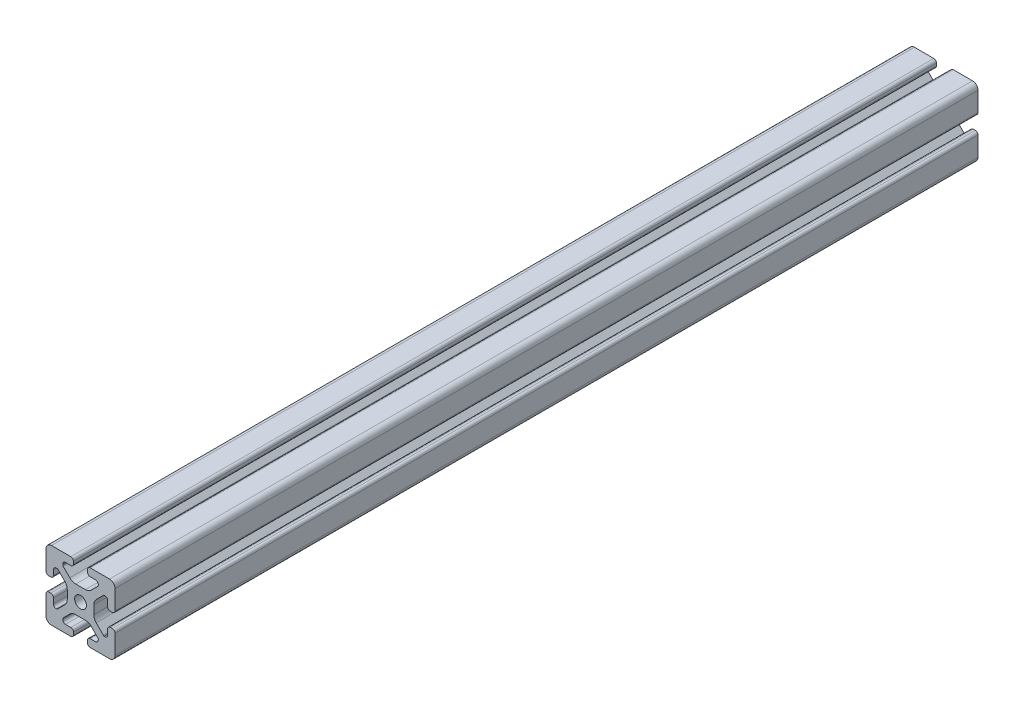
SolidWorks part; units mm, degrees
ref_plane "Front Plane" through (0, 0, 0) normal (0, 0, 1) x (1, 0, 0)
ref_plane "Top Plane" through (0, 0, 0) normal (0, 1, 0) x (1, 0, 0)
ref_plane "Right Plane" through (0, 0, 0) normal (1, 0, 0) x (0, 0, -1)
sketch "Sketch1" plane through (0, 0, 0) normal (0, 0, 1) x (1, 0, 0)
  line L0 (0, 19.7407) -> (0, -19.7407) construction
  line L1 (19.0335, 0) -> (-20.7246, 0) construction
  line L2 (-8.715, -15.5246) -> (-5.63, -15.5246)
  line L3 (-10.285, -13.9546) -> (-10.285, -13.4925)
  line L4 (-6.2171, -9.1098) -> (-10.0624, -12.9551)
  line L5 (2.7773, -7.685) -> (-2.7773, -7.685)
  line L6 (10.0624, -12.9551) -> (6.2171, -9.1098)
  line L7 (10.285, -13.9546) -> (10.285, -13.4925)
  line L8 (5.63, -15.5246) -> (8.715, -15.5246)
  line L9 (4.06, -18.43) -> (4.06, -17.0946)
  line L10 (-4.06, -18.43) -> (-4.06, -17.0946)
  line L11 (15.68, -8.7154) -> (15.68, -5.63)
  line L12 (-14.11, -10.2854) -> (-13.8169, -10.2854)
  line L13 (20, -16.83) -> (20, -5.63)
  line L14 (20, 5.63) -> (20, 13.0011)
  line L15 (-16.83, 20) -> (-5.63, 20)
  line L16 (5.63, 20) -> (12.9796, 20)
  line L17 (-8.715, 15.5246) -> (-5.63, 15.5246)
  line L18 (-20, -17.0184) -> (-20, -5.7579)
  line L19 (-20, 5.573) -> (-20, 13.0045)
  line L20 (-15.68, -8.7154) -> (-15.68, -5.7579)
  line L21 (-16.6746, -20) -> (-5.63, -20)
  line L22 (5.63, -20) -> (13, -20)
  line L23 (14.11, -10.2854) -> (13.6201, -10.2854)
  line L24 (13.1637, -9.947) -> (9.0762, -5.8595)
  line L25 (7.685, -2.5008) -> (7.685, 2.5008)
  line L26 (9.0762, 5.8595) -> (13.2795, 10.0628)
  line L27 (13.8169, 10.2854) -> (14.11, 10.2854)
  line L28 (15.68, 8.7154) -> (15.68, 5.63)
  line L29 (17.25, 4.06) -> (18.43, 4.06)
  line L30 (20, 13.0011) -> (20, 16.83)
  line L31 (16.83, 20) -> (12.9796, 20)
  line L32 (4.06, 18.43) -> (4.06, 17.0946)
  line L33 (5.63, 15.5246) -> (8.715, 15.5246)
  line L34 (10.285, 13.9546) -> (10.285, 13.4925)
  line L35 (10.0624, 12.9551) -> (6.2171, 9.1098)
  line L36 (2.7773, 7.685) -> (-2.7773, 7.685)
  line L37 (-6.2171, 9.1098) -> (-10.0624, 12.9551)
  line L38 (-10.285, 13.4925) -> (-10.285, 13.9546)
  line L39 (-4.06, 17.0946) -> (-4.06, 18.43)
  line L40 (-20, 16.83) -> (-20, 13.0045)
  line L41 (-18.43, 4.003) -> (-17.25, 4.003)
  line L42 (-15.68, 5.573) -> (-15.68, 8.4757)
  line L43 (-14.0552, 10.0447) -> (-13.7199, 10.033)
  line L44 (-13.0405, 9.8238) -> (-9.0762, 5.8595)
  line L45 (-7.685, 2.5008) -> (-7.685, -2.5008)
  line L46 (-9.0762, -5.8595) -> (-13.2795, -10.0628)
  line L47 (-17.2485, -4.1204) -> (-18.43, -4.1204)
  line L48 (13, -20) -> (16.83, -20)
  line L49 (18.43, -4.06) -> (17.25, -4.06)
  arc A0 (-5.63, -15.5246) -> (-4.06, -17.0946) centre (-5.63, -17.0946) cw
  arc A1 (-8.715, -15.5246) -> (-10.285, -13.9546) centre (-8.715, -13.9546) cw
  arc A2 (-10.285, -13.4925) -> (-10.0624, -12.9551) centre (-9.525, -13.4925) cw
  arc A3 (-6.2171, -9.1098) -> (-2.7773, -7.685) centre (-2.7773, -12.5496) cw
  arc A4 (2.7773, -7.685) -> (6.2171, -9.1098) centre (2.7773, -12.5496) cw
  arc A5 (10.0624, -12.9551) -> (10.285, -13.4925) centre (9.525, -13.4925) cw
  arc A6 (10.285, -13.9546) -> (8.715, -15.5246) centre (8.715, -13.9546) cw
  arc A7 (4.06, -17.0946) -> (5.63, -15.5246) centre (5.63, -17.0946) cw
  arc A8 (5.63, -20) -> (4.06, -18.43) centre (5.63, -18.43) cw
  arc A9 (-4.06, -18.43) -> (-5.63, -20) centre (-5.63, -18.43) cw
  circle A10 centre (0, 0) radius 3.4
  arc A11 (17.25, -4.06) -> (15.68, -5.63) centre (17.25, -5.63) ccw
  arc A12 (14.11, -10.2854) -> (15.68, -8.7154) centre (14.11, -8.7154) ccw
  arc A13 (13.1637, -9.947) -> (13.6201, -10.2854) centre (13.8117, -9.55) ccw
  arc A14 (7.685, -2.5008) -> (9.0762, -5.8595) centre (12.435, -2.5008) ccw
  arc A15 (9.0762, 5.8595) -> (7.685, 2.5008) centre (12.435, 2.5008) ccw
  arc A16 (13.8169, 10.2854) -> (13.2795, 10.0628) centre (13.8169, 9.5254) ccw
  arc A17 (15.68, 8.7154) -> (14.11, 10.2854) centre (14.11, 8.7154) ccw
  arc A18 (15.68, 5.63) -> (17.25, 4.06) centre (17.25, 5.63) ccw
  arc A19 (18.43, 4.06) -> (20, 5.63) centre (18.43, 5.63) ccw
  arc A20 (20, 16.83) -> (16.83, 20) centre (16.83, 16.83) ccw
  arc A21 (5.63, 20) -> (4.06, 18.43) centre (5.63, 18.43) ccw
  arc A22 (4.06, 17.0946) -> (5.63, 15.5246) centre (5.63, 17.0946) ccw
  arc A23 (10.285, 13.9546) -> (8.715, 15.5246) centre (8.715, 13.9546) ccw
  arc A24 (10.0624, 12.9551) -> (10.285, 13.4925) centre (9.525, 13.4925) ccw
  arc A25 (2.7773, 7.685) -> (6.2171, 9.1098) centre (2.7773, 12.5496) ccw
  arc A26 (-6.2171, 9.1098) -> (-2.7773, 7.685) centre (-2.7773, 12.5496) ccw
  arc A27 (-10.285, 13.4925) -> (-10.0624, 12.9551) centre (-9.525, 13.4925) ccw
  arc A28 (-8.715, 15.5246) -> (-10.285, 13.9546) centre (-8.715, 13.9546) ccw
  arc A29 (-5.63, 15.5246) -> (-4.06, 17.0946) centre (-5.63, 17.0946) ccw
  arc A30 (-4.06, 18.43) -> (-5.63, 20) centre (-5.63, 18.43) ccw
  arc A31 (-16.83, 20) -> (-20, 16.83) centre (-16.83, 16.83) ccw
  arc A32 (-20, 5.573) -> (-18.43, 4.003) centre (-18.43, 5.573) ccw
  arc A33 (-17.25, 4.003) -> (-15.68, 5.573) centre (-17.25, 5.573) ccw
  arc A34 (-14.0552, 10.0447) -> (-15.68, 8.4757) centre (-14.11, 8.4757) ccw
  arc A35 (-13.0405, 9.8238) -> (-13.7199, 10.033) centre (-13.5779, 9.2864) ccw
  arc A36 (-7.685, 2.5008) -> (-9.0762, 5.8595) centre (-12.435, 2.5008) ccw
  arc A37 (-9.0762, -5.8595) -> (-7.685, -2.5008) centre (-12.435, -2.5008) ccw
  arc A38 (-13.8169, -10.2854) -> (-13.2795, -10.0628) centre (-13.8169, -9.5254) ccw
  arc A39 (-15.68, -8.7154) -> (-14.11, -10.2854) centre (-14.11, -8.7154) ccw
  arc A40 (-15.68, -5.7579) -> (-17.2485, -4.1204) centre (-17.2485, -5.6904) ccw
  arc A41 (-18.43, -4.1204) -> (-20, -5.7579) centre (-18.4315, -5.6904) ccw
  arc A42 (-20, -17.0184) -> (-16.6746, -20) centre (-16.8354, -16.8341) ccw
  arc A43 (16.83, -20) -> (20, -16.83) centre (16.83, -16.83) ccw
  arc A44 (20, -5.63) -> (18.43, -4.06) centre (18.43, -5.63) ccw
  dimension "D1" = 6.8
  dimension "D2" = 4.32
  dimension "D3" = 15.37
  dimension "D4" = 20.57
  dimension "D5" = 15.37
  dimension "D6" = 40
  dimension "D7" = 20
  dimension "D8" = 4.32
  dimension "D9" = 8.12
extrude "Boss-Extrude2" add sketch "Sketch1" along normal blind 500
